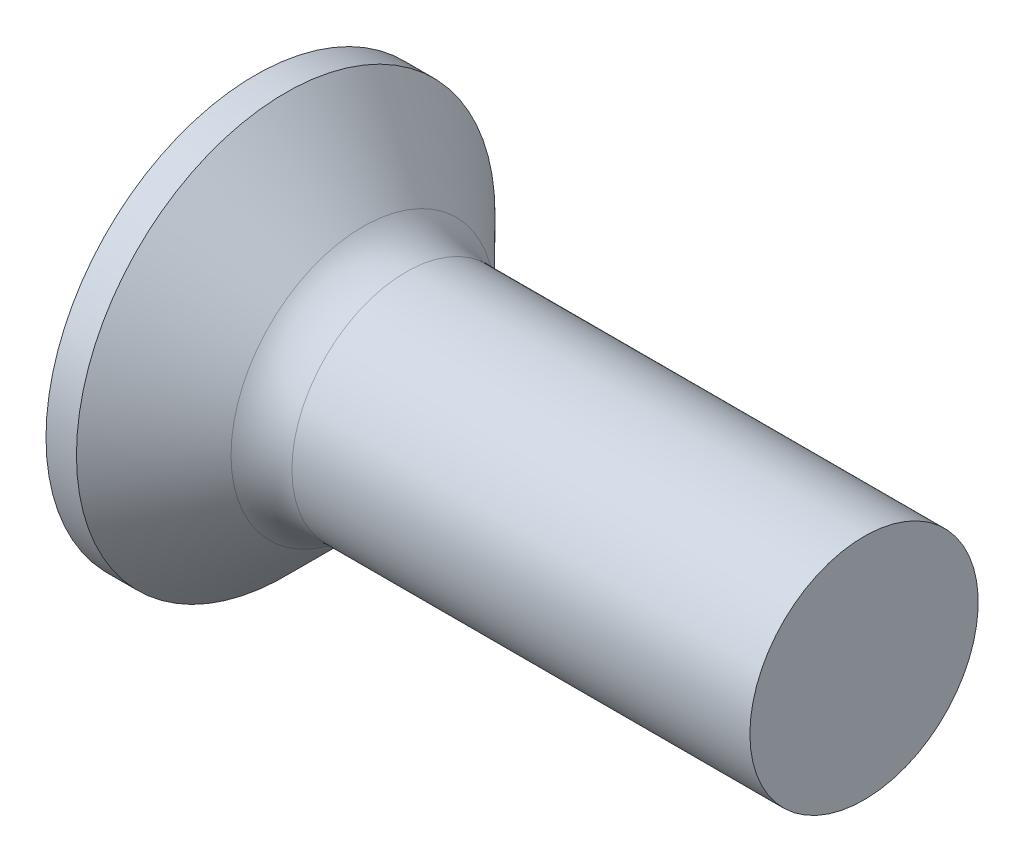
SolidWorks part; units mm, degrees
revolve "Base-Revolve" add sketch "BodySke" angle 360 about L5
sketch "BodySke" plane through (0, 0, 0) normal (0, 0, 1) x (1, 0, 0)
  line L0 (0, 0) -> (0, 2.75)
  line L1 (0, 2.75) -> (0.4, 2.75)
  line L2 (1.65, 1.5) -> (8, 1.5)
  line L3 (8, 1.5) -> (8, 0)
  line L4 (8, 0) -> (0, 0)
  line L5 (-6.35, 0) -> (82.55, 0) construction
  line L6 (1.65, -1.5) -> (8, -1.5) construction
  line L7 (0.4, -2.75) -> (1.65, -1.5) construction
  line L8 (0.4, 2.75) -> (1.65, 1.5)
  line L9 (0, -2.75) -> (0.4, -2.75) construction
  line L10 (2.15, 3.0875) -> (2.15, -6.4375) construction
  line L11 (0, 6.35) -> (0, -3.175) construction
  dimension "Diameter" = 3
  dimension "Head_ht" = 1.65
  dimension "Head_dia" = 5.5
  dimension "Head_ang" = 90
  dimension "D6" = 0.4
  dimension "Advance" = 0.5
cosmetic thread "ThreadCosmetic" [suppressed] parameters "Thread_length"=3.85, "Thread_minor"=2.439
ref_plane "Plane1" through (0, 0, 0) normal (0, 0, 1) x (1, 0, 0)
ref_plane "Plane2" through (0, 0, 0) normal (0, 1, 0) x (1, 0, 0)
ref_plane "Plane3" through (0, 0, 0) normal (1, 0, 0) x (0, 0, -1)
other "Configuration Table"
fillet "Fillet1" radius 0.8 1 edges at (1.65, 0, 1.5)
sketch "Sketch3" plane through (0, 0, 0) normal (-1, 0, 0) x (0, 0, 1)
  line L0 (-0.37, 1.5) -> (0.37, 1.5)
  line L1 (0.37, 1.5) -> (0.37, -1.5)
  line L2 (0.37, -1.5) -> (-0.37, -1.5)
  line L3 (-0.37, -1.5) -> (-0.37, 1.5)
  dimension "Cross_dia" = 3
  dimension "Cross_width" = 0.74
  dimension "D1" = 1.5
  dimension "D2" = 0.37
ref_plane "Plane4" through (2.01, 0, 0) normal (-1, 0, 0) x (0, 0, 1)
sketch "Sketch4" plane through (2.01, 0, 0) normal (-1, 0, 0) x (0, 0, 1)
  line L0 (-0.37, 0.4979) -> (0.37, 0.4979)
  line L3 (0.37, 0.4979) -> (0.37, -0.4979)
  line L4 (0.37, -0.4979) -> (-0.37, -0.4979)
  line L5 (-0.37, -0.4979) -> (-0.37, 0.4979)
  dimension "D2" = 0.9957
  dimension "D1" = 0.74
  dimension "D4" = 0.4979
  dimension "D3" = 0.37
loft "Recess" cut profiles "Sketch3", "Sketch4"
pattern_circular "RecPat" count 2 every 90 about axis through (0, 0, 0) along (1, 0, 0) of "Recess"
sketch "RecCorSke" plane through (0, 0, 0) normal (0, 0, 1) x (1, 0, 0)
  line L0 (-3.175, 0) -> (15.875, 0) construction
  line L2 (0, 0) -> (0, 0.6966)
  line L3 (0, 0.6966) -> (2.01, 0.556)
  line L4 (2.01, 0.556) -> (2.1907, 0)
  line L5 (2.1907, 0) -> (0, 0)
  dimension "Diameter" = 1.112
  dimension "Depth" = 2.01
  dimension "Draft_angle" = 4
  dimension "Bottom_angle" = 18
revolve "RecessCore" cut sketch "RecCorSke" angle 360 about L0
sketch "ThdSchSke" plane through (0, 0, 0) normal (0, 0, 1) x (1, 0, 0)
  line L0 (2.15, -1.2195) -> (1.9536, -1.5)
  line L1 (2.15, -1.2195) -> (2.3464, -1.5)
  line L2 (2.3464, -1.5) -> (2.3464, -1.875)
  line L3 (-3.175, 0) -> (5.1513, 0) construction
  line L5 (2.3464, -1.875) -> (1.9536, -1.875)
  line L6 (1.9536, -1.875) -> (1.9536, -1.5)
  line L7 (0, 2.75) -> (0, -2.75) construction
  dimension "Diameter" = 3
  dimension "Thread_minor" = 2.439
  dimension "Start" = 2.15
revolve "ThreadSchematic" [suppressed] cut sketch "ThdSchSke" angle 360 about L3
pattern_linear "ThdSchPat" [suppressed]
equation "\"D1@Sketch3\" = \"Cross_dia@Sketch3\" / 2"
equation "\"D2@Sketch3\" = \"Cross_width@Sketch3\" / 2"
equation "\"Depth@RecCorSke\" = \"Cross_depth@Plane4\""
equation "\"D1@Sketch4\" = \"Cross_width@Sketch3\""
equation "\"D2@Sketch4\" = \"Cross_dia@Sketch3\" - 2.0 * \"Cross_depth@Plane4\" * tan(26.5  * 0.017453292)"
equation "\"D3@Sketch4\" = \"D1@Sketch4\" / 2"
equation "\"D4@Sketch4\" = \"D2@Sketch4\" / 2"
equation "\"Thread_length@ThreadCosmetic\" = ((sgn( (\"Length@BodySke\" - \"Advance@BodySke\" * 1.0 - \"Head_ht@BodySke\" ) - \"Thread_nom@BodySke\" )-1)*( (\"Length@BodySke\" - \"Advance@BodySke\" * 1.0 - \"Head_ht@BodySke\" ) - \"Thread_nom@BodySke\" ))/-2+ \"Thread_nom@BodySke\""
equation "\"Thread_minor@ThdSchSke\" = \"Thread_minor@ThreadCosmetic\""
equation "\"Diameter@ThdSchSke\" = \"Diameter@BodySke\""
equation "\"Overcut@ThdSchSke\" = \"Diameter@BodySke\" * 1.25"
equation "\"Start@ThdSchSke\" = 0.000001 + \"Length@BodySke\" - \"Thread_length@ThreadCosmetic\"  '---Countersunk---"
equation "\"Num_threads@ThdSchPat\" = int( \"Thread_length@ThreadCosmetic\" / \"Advance@BodySke\" + 0.999 )  + 1"
equation "\"Advance@ThdSchPat\" = \"Thread_length@ThreadCosmetic\" /  (\"Num_threads@ThdSchPat\" - 1) 'relax it"
